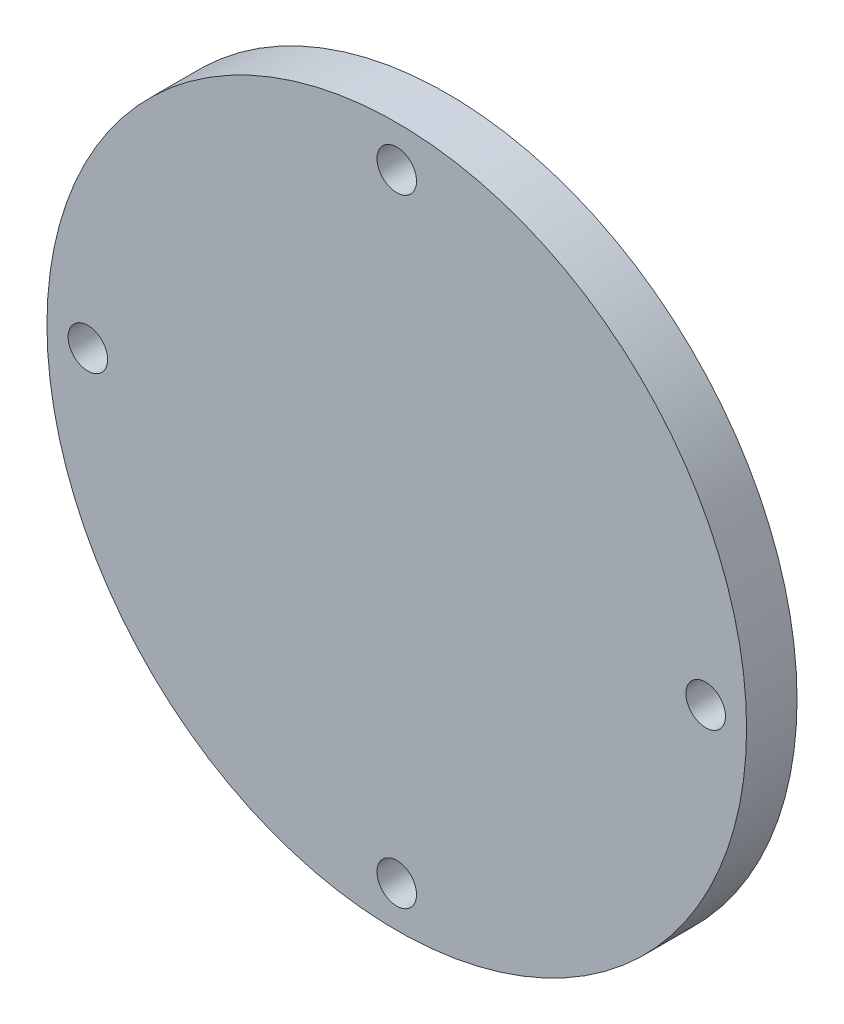
SolidWorks part; units mm, degrees
ref_plane "Front Plane" through (0, 0, 0) normal (0, 0, 1) x (1, 0, 0)
ref_plane "Top Plane" through (0, 0, 0) normal (0, 1, 0) x (1, 0, 0)
ref_plane "Right Plane" through (0, 0, 0) normal (1, 0, 0) x (0, 0, -1)
sketch "Sketch1" plane through (0, 0, 0) normal (0, 0, 1) x (1, 0, 0)
  circle A0 centre (0, 0) radius 25.65
  circle A2 centre (0, -22.65) radius 1.45
  circle A3 centre (0, -22.65) radius 1.45
  circle A4 centre (22.65, 0) radius 1.45
  circle A5 centre (22.65, 0) radius 1.45
  circle A6 centre (0, 22.65) radius 1.45
  circle A7 centre (0, 22.65) radius 1.45
  circle A8 centre (-22.65, 0) radius 1.45
  circle A9 centre (-22.65, 0) radius 1.45
  dimension "D1" = 0
  dimension "D2" = 0
  dimension "D3" = 0
  dimension "D4" = 0
extrude "Boss-Extrude1" add sketch "Sketch1" along normal blind 3.7
